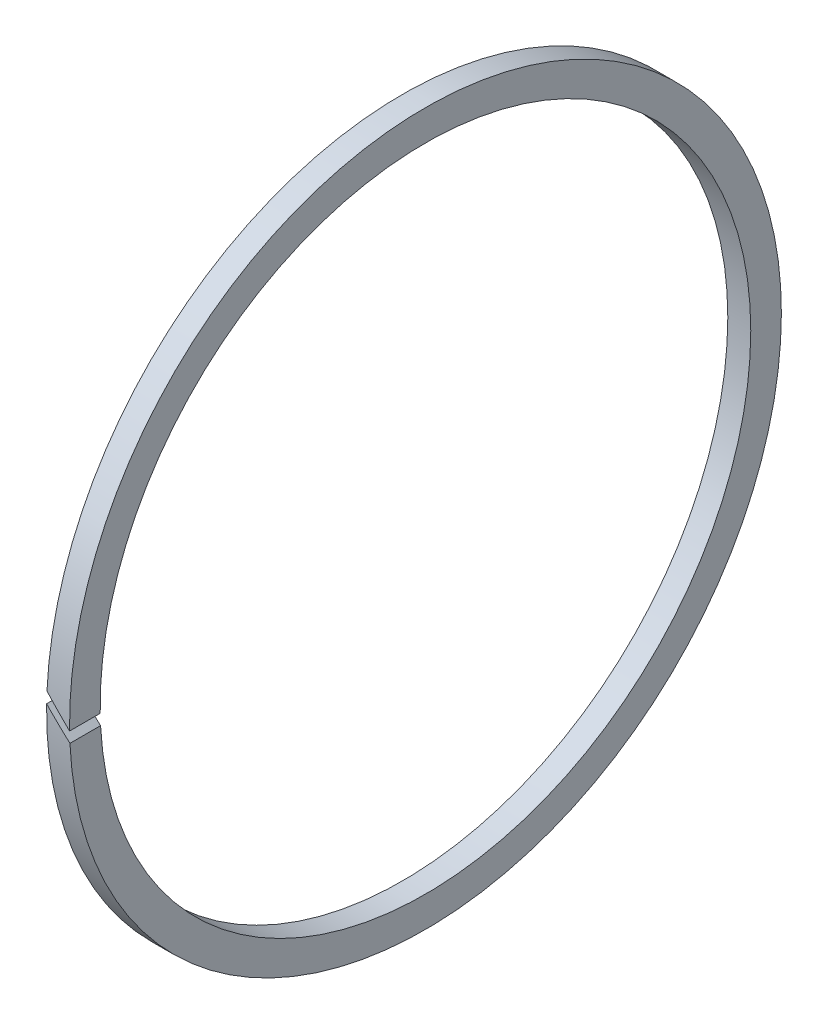
SolidWorks part; units mm, degrees
ref_plane "Front Plane" through (0, 0, 0) normal (0, 0, 1) x (1, 0, 0)
ref_plane "Top Plane" through (0, 0, 0) normal (0, 1, 0) x (1, 0, 0)
ref_plane "Right Plane" through (0, 0, 0) normal (1, 0, 0) x (0, 0, -1)
sketch "Sketch1" plane through (0, 0, 0) normal (0, 0, 1) x (1, 0, 0)
  line L0 (0, 0) -> (10762.8753, 0) construction
  line L1 (0, 0) -> (0, 10762.8753) construction
  line L2 (0, 46.5) -> (3, 46.5)
  line L3 (3, 46.5) -> (3, 42.5)
  line L4 (3, 42.5) -> (0, 42.5)
  line L5 (0, 42.5) -> (0, 46.5)
  dimension "D1" = 3
  dimension "D2" = 42.5
  dimension "D3" = 46.5
revolve "Revolve1" add sketch "Sketch1" angle 360 about L0
sketch "Sketch5" plane through (0, 0, 0) normal (0, 0, 1) x (1, 0, 0)
  line L0 (1.5, -46.5) -> (1.5, 49953.5) construction
  line L1 (0, -46.5) -> (3, -46.5) construction
  line L2 (0, 0) -> (50000, 0) construction
  line L3 (0, 46.5) -> (0, -46.5) construction
  line L4 (-1.6932, 2.4861) -> (3.9861, -3.1932)
  line L5 (-1.6932, 2.4861) -> (-0.9861, 3.1932)
  line L6 (3.9861, -3.1932) -> (4.6932, -2.4861)
  line L7 (-0.9861, 3.1932) -> (4.6932, -2.4861)
  line L8 (-1.6932, 2.4861) -> (4.6932, -2.4861) construction
  line L9 (3.9861, -3.1932) -> (-0.9861, 3.1932) construction
  point P4 (1.5, -46.5)
  point P10 (0, 0)
  point P12 (1.5, 0)
  dimension "D1" = 1
  dimension "D2" = 45
extrude "Cut-Extrude2" cut sketch "Sketch5" along normal up to next
